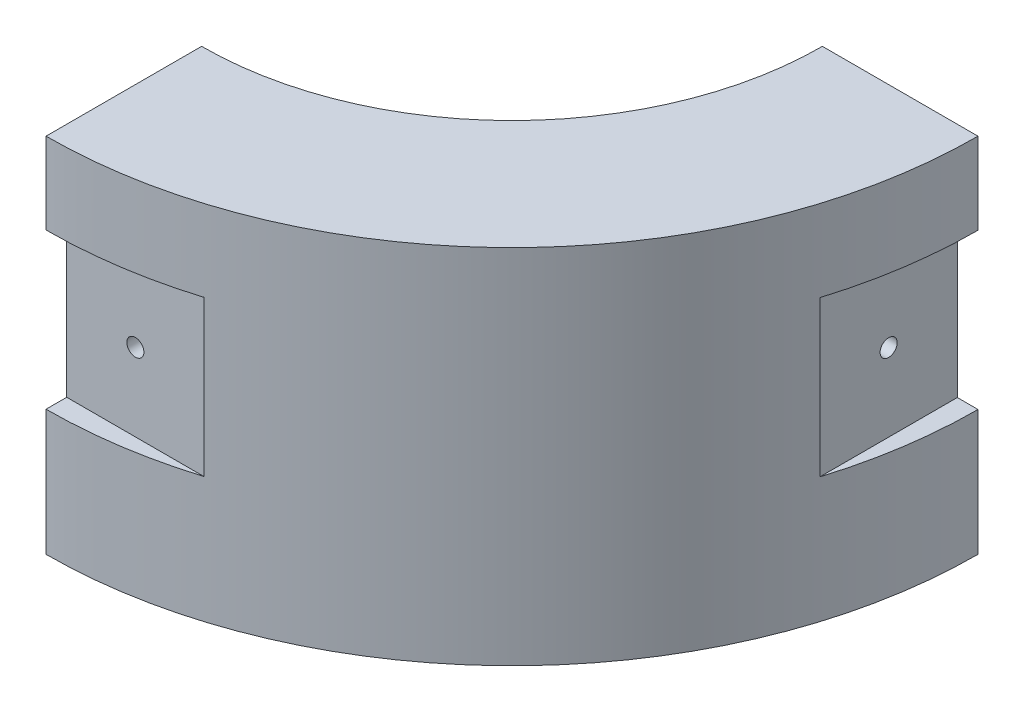
SolidWorks part; units mm, degrees
ref_plane "Front Plane" through (0, 0, 0) normal (0, 0, 1) x (1, 0, 0)
ref_plane "Top Plane" through (0, 0, 0) normal (0, 1, 0) x (1, 0, 0)
ref_plane "Right Plane" through (0, 0, 0) normal (1, 0, 0) x (0, 0, -1)
sketch "Sketch1" plane through (0, 0, 0) normal (0, 1, 0) x (1, 0, 0)
  line L0 (0, 0) -> (168.7568, 0) construction
  line L1 (168.7568, 0) -> (0, 0) construction
  line L2 (0, 0) -> (0, -120.649) construction
  line L3 (75, 0) -> (90.075, 0)
  line L4 (0, -75) -> (0, -90.075)
  arc A0 (0, -90.075) -> (90.075, 0) centre (0, 0) ccw
  arc A1 (0, -75) -> (75, 0) centre (0, 0) ccw
  dimension "D1" = 180.15
  dimension "D2" = 150
extrude "Base_Wall" add sketch "Sketch1" along normal blind 70
sketch "Sketch3" plane through (0, 70, 0) normal (0, 1, 0) x (1, 0, 0)
  line L0 (0, 0) -> (-73.6387, 0) construction
  line L1 (-73.6387, 0) -> (0, 0) construction
  line L2 (0, 0) -> (0, -90.075) construction
  line L3 (0, 0) -> (0, 60) construction
  line L4 (0, 60) -> (0, 0) construction
  line L5 (0, 0) -> (90.734, 0) construction
  line L6 (0, -75) -> (0, -60)
  line L7 (75, 0) -> (60, 0)
  arc A0 (0, -75) -> (75, 0) centre (0, 0) ccw
  arc A1 (0, -60) -> (60, 0) centre (0, 0) ccw
  dimension "D1" = 150
  dimension "D2" = 120
extrude "Base_Support" add sketch "Sketch3" against normal blind 61.5
sketch "Sketch4" plane through (0, 0, 0) normal (0, 0, -1) x (-1, 0, 0)
  line L0 (-90.075, 70) -> (-60, 8.5) construction
  line L1 (-60, 8.5) -> (-60, 70) construction
  line L2 (-60, 70) -> (-90.075, 8.5) construction
  line L3 (-90.075, 70) -> (-90.075, 0) construction
  line L4 (-90.075, 8.5) -> (-60, 8.5) construction
  line L5 (-75.0375, 39.25) -> (-90.075, 39.25) construction
  line L7 (-94.075, 24.25) -> (-86.075, 24.25)
  line L8 (-94.075, 24.25) -> (-94.075, 54.25)
  line L9 (-94.075, 54.25) -> (-86.075, 54.25)
  line L10 (-86.075, 24.25) -> (-86.075, 54.25)
  line L11 (-94.075, 24.25) -> (-86.075, 54.25) construction
  line L12 (-94.075, 54.25) -> (-86.075, 24.25) construction
  dimension "D1" = 30
  dimension "D2" = 4
extrude "Mount-Notch" cut sketch "Sketch4" against normal blind 61.5
sketch "Sketch5" plane through (0, 0, 0) normal (1, 0, 0) x (0, 0, -1)
  line L0 (-26.5443, 54.25) -> (0, 24.25) construction
  line L1 (0, 24.25) -> (0, 0) construction
  line L2 (0, 24.25) -> (0, 54.25) construction
  line L3 (0, 24.25) -> (-26.5443, 24.25) construction
  line L4 (-26.5443, 24.25) -> (0, 54.25) construction
  circle A0 centre (-13.2722, 39.25) radius 1.65
  dimension "D1" = 3.3
extrude "Screw-Hole-M3" cut sketch "Sketch5" along normal blind 181.5
sketch "Sketch6" plane through (0, 0, 0) normal (-1, 0, 0) x (0, 0, 1)
  line L0 (60, 70) -> (90.075, 8.5885) construction
  line L1 (90.075, 70) -> (90.075, 0) construction
  line L2 (90.075, 8.5885) -> (60, 8.5885) construction
  line L3 (60, 8.5) -> (60, 70) construction
  line L4 (60, 8.5885) -> (90.075, 70) construction
  line L5 (75.0375, 39.2943) -> (90.075, 39.2943) construction
  line L7 (86.075, 24.2943) -> (94.075, 24.2943)
  line L8 (86.075, 24.2943) -> (86.075, 54.2943)
  line L9 (86.075, 54.2943) -> (94.075, 54.2943)
  line L10 (94.075, 24.2943) -> (94.075, 54.2943)
  line L11 (86.075, 24.2943) -> (94.075, 54.2943) construction
  line L12 (86.075, 54.2943) -> (94.075, 24.2943) construction
  dimension "D1" = 30
  dimension "D2" = 4
extrude "Cut-Extrude4" cut sketch "Sketch6" against normal blind 181.5
sketch "Sketch7" plane through (0, 0, 86.075) normal (0, 0, 1) x (1, 0, 0)
  line L0 (0, 54.2943) -> (26.5443, 24.2943) construction
  line L1 (26.5443, 24.2943) -> (26.5443, 54.2943) construction
  line L2 (26.5443, 54.2943) -> (0, 24.2943) construction
  circle A0 centre (13.2722, 39.2943) radius 1.65
  dimension "D1" = 3.3
extrude "Cut-Extrude5" cut sketch "Sketch7" against normal blind 181.5
